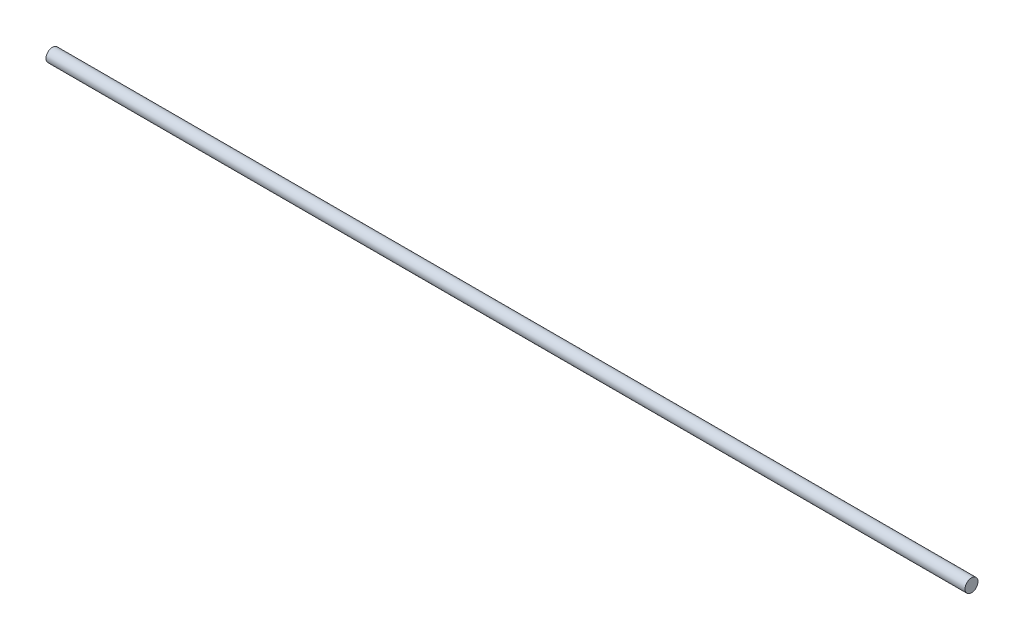
SolidWorks part; units mm, degrees
material "6061-T6 (SS)"
ref_plane "Front Plane" through (0, 0, 0) normal (1, 0, 0) x (0, 1, 0)
ref_plane "Top Plane" through (0, 0, 0) normal (0, 0, 1) x (0, 1, 0)
ref_plane "Right Plane" through (0, 0, 0) normal (0, 1, 0) x (-1, 0, 0)
sketch "Sketch1" plane through (0, 0, 0) normal (1, 0, 0) x (0, 1, 0)
  circle A0 centre (0, 0) radius 6.35
  dimension "D1" = 12.7
extrude "Boss-Extrude1" add sketch "Sketch1" along normal blind 898.3927 contours A0
equation "\"d\"= 0.5in"
equation "\"E\"= 10007604"
equation "\"F\"= 500"
equation "\"delta_max\"= 0.009"
equation "\"A\"= ( pi * ( \"d\" ^ 2 ) ) / 4"
equation "\"L\"= ( \"delta_max\" * \"A\" * \"E\" ) / \"F\""
equation "\"D1@Sketch1\"= \"d\""
equation "\"D1@Boss-Extrude1\"= \"L\""
